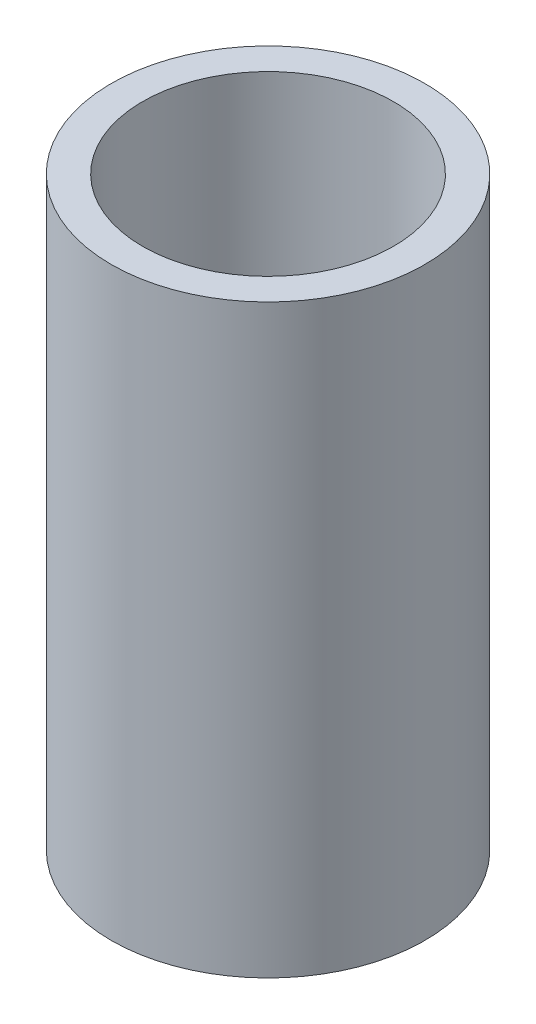
SolidWorks part; units mm, degrees
ref_plane "Front Plane" through (0, 0, 0) normal (0, 0, 1) x (1, 0, 0)
ref_plane "Top Plane" through (0, 0, 0) normal (0, 1, 0) x (1, 0, 0)
ref_plane "Right Plane" through (0, 0, 0) normal (1, 0, 0) x (0, 0, -1)
sketch "Sketch1" plane through (0, 0, 0) normal (0, 1, 0) x (1, 0, 0)
  circle A0 centre (0, 0) radius 7.5
  circle A1 centre (0, 0) radius 6
  dimension "D1" = 15
  dimension "D2" = 12
extrude "Boss-Extrude1" add sketch "Sketch1" along normal blind 28
